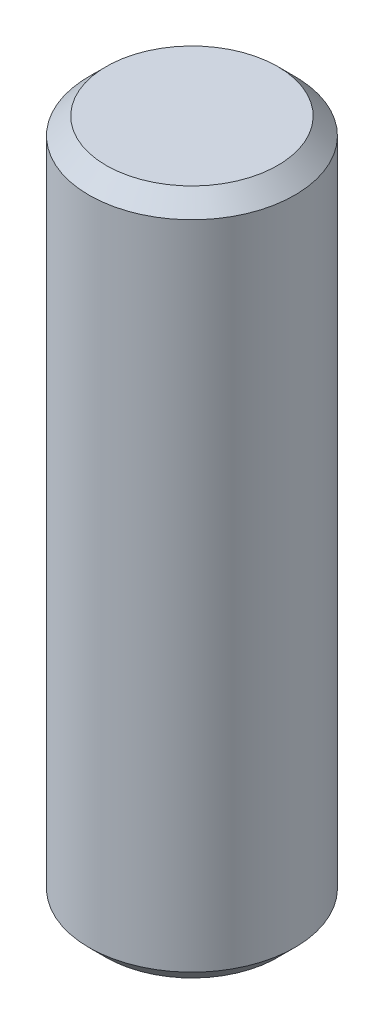
SolidWorks part; units mm, degrees
ref_plane "Front Plane" through (0, 0, 0) normal (0, 0, 1) x (1, 0, 0)
ref_plane "Top Plane" through (0, 0, 0) normal (0, 1, 0) x (1, 0, 0)
ref_plane "Right Plane" through (0, 0, 0) normal (1, 0, 0) x (0, 0, -1)
sketch "Sketch1" plane through (0, 0, 0) normal (0, 1, 0) x (1, 0, 0)
  circle A0 centre (0, 0) radius 3
  dimension "D1" = 6
extrude "Boss-Extrude1" add sketch "Sketch1" along normal mid plane 20
chamfer "Chamfer1" distance 0.5 angle 45 2 edges at (0, -10, 3) (0, 10, 3)
